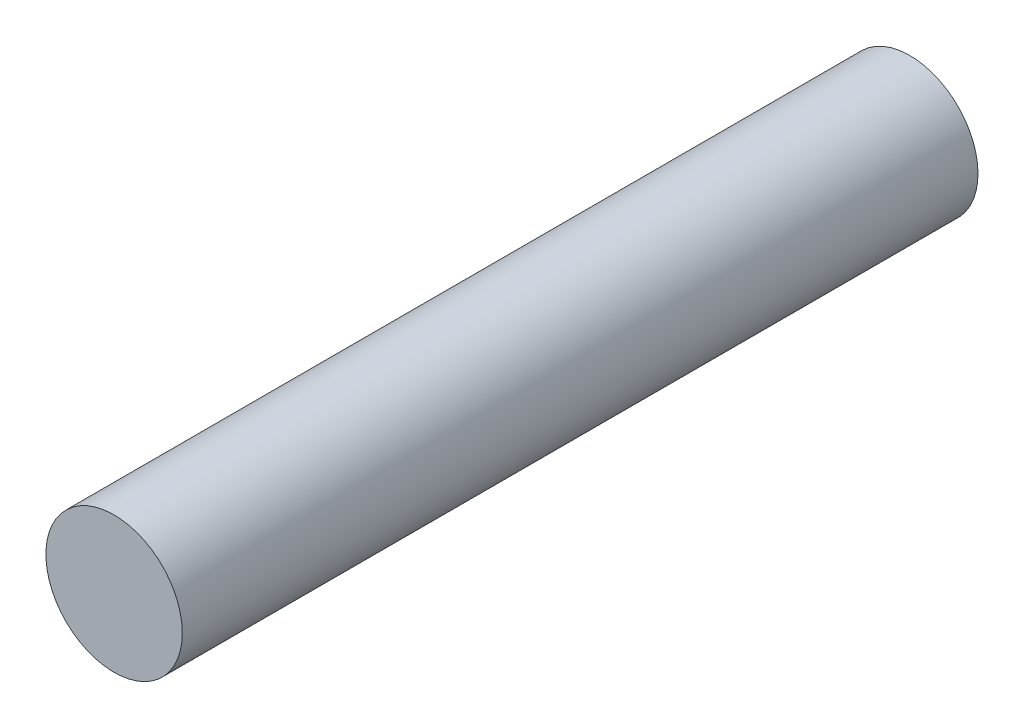
SolidWorks part; units mm, degrees
ref_plane "Front Plane" through (0, 0, 0) normal (0, 0, 1) x (1, 0, 0)
ref_plane "Top Plane" through (0, 0, 0) normal (0, 1, 0) x (1, 0, 0)
ref_plane "Right Plane" through (0, 0, 0) normal (1, 0, 0) x (0, 0, -1)
sketch "Sketch1" plane through (0, 0, 0) normal (0, 0, 1) x (1, 0, 0)
  circle A0 centre (0, 0) radius 3
  dimension "D1" = 6
extrude "Boss-Extrude1" add sketch "Sketch1" along normal mid plane 35
